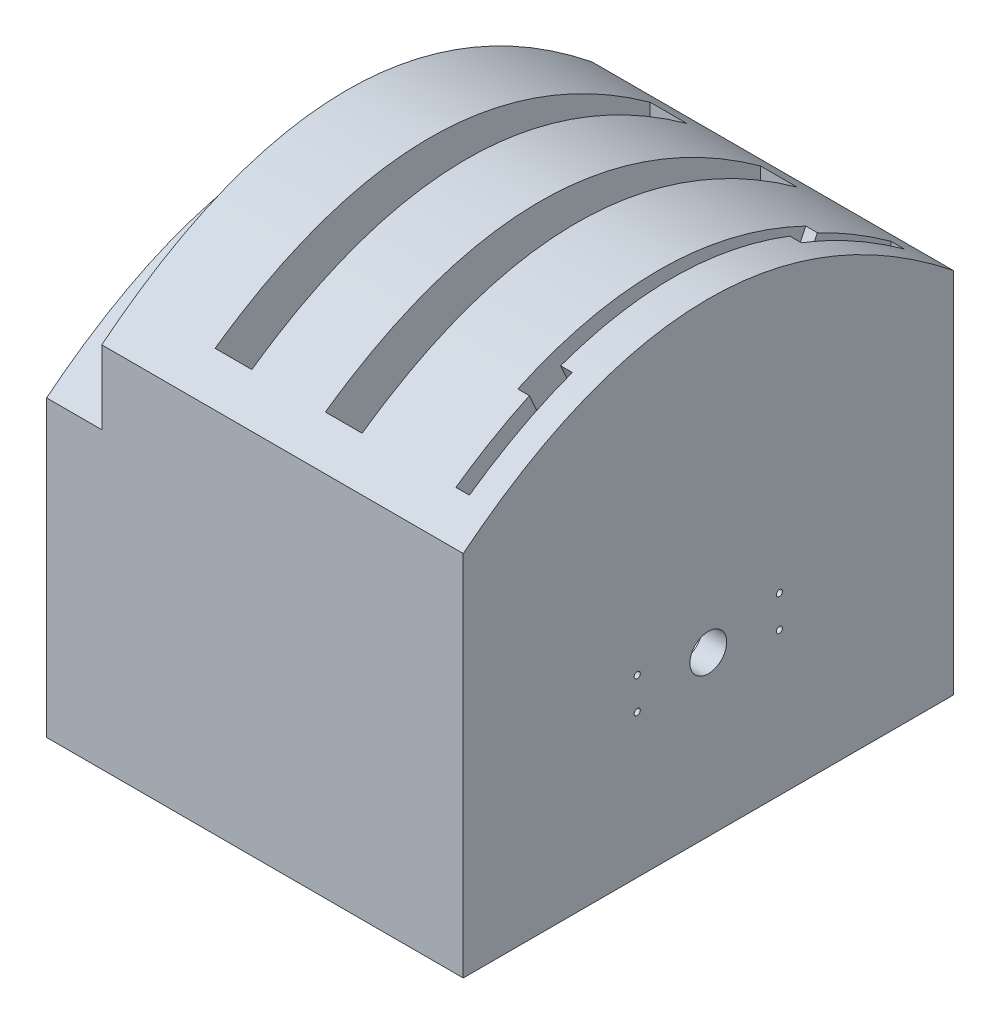
SolidWorks part; units mm, degrees
ref_plane "Front Plane" through (0, 0, 0) normal (0, 0, 1) x (1, 0, 0)
ref_plane "Top Plane" through (0, 0, 0) normal (0, 1, 0) x (1, 0, 0)
ref_plane "Right Plane" through (0, 0, 0) normal (1, 0, 0) x (0, 0, -1)
sketch "Sketch1" plane through (0, 0, 0) normal (1, 0, 0) x (0, 0, -1)
  line L2 (-100, 85) -> (-100, -65)
  line L3 (-100, -65) -> (100, -65)
  line L4 (100, 85) -> (100, -65)
  spline S0 degree 2 poles (-100, 85) (0, 165) (100, 85) knots 0 0 0 1 1 1
  point P4 (-100, 85)
  point P5 (100, 85)
  dimension "D1" = 200
  dimension "D2" = 100
  dimension "D3" = 150
  dimension "D4" = 150
  dimension "D5" = 40
  dimension "D6" = 100
  dimension "D7" = 125
extrude "Base" add sketch "Sketch1" along normal blind 170
ref_plane "New Top" through (0, 125, 0) normal (0, 1, 0) x (1, 0, 0)
sketch "Sketch3" plane through (0, 125, 0) normal (0, 1, 0) x (1, 0, 0)
  line L0 (170, -100) -> (170, 100) construction
  line L1 (116.25, 90) -> (101.25, 90)
  line L2 (116.25, 90) -> (116.25, -87.5)
  line L3 (116.25, -87.5) -> (101.25, -87.5)
  line L4 (101.25, 90) -> (101.25, -87.5)
  line L7 (170, 100) -> (0, 100) construction
  line L8 (71.25, 90) -> (56.25, 90)
  line L9 (71.25, 90) -> (71.25, -87.5)
  line L10 (71.25, -87.5) -> (56.25, -87.5)
  line L11 (56.25, 90) -> (56.25, -87.5)
  line L12 (170, -100) -> (0, -100) construction
  dimension "D1" = 53.75
  dimension "D2" = 15
  dimension "D3" = 30
  dimension "D4" = 15
  dimension "D5" = 10
  dimension "D6" = 12.5
  dimension "D7" = 12.5
  dimension "D8" = 10
sketch "Sketch4" plane through (0, 125, 0) normal (0, 1, 0) x (1, 0, 0)
  line L1 (22.5, 87.5) -> (10, 87.5)
  line L2 (22.5, 87.5) -> (22.5, -87.5)
  line L3 (22.5, -87.5) -> (10, -87.5)
  line L4 (10, 87.5) -> (10, -87.5)
  line L5 (170, 100) -> (0, 100) construction
  line L6 (170, -100) -> (0, -100) construction
  line L7 (0, 100) -> (0, -100) construction
  dimension "D1" = 10
  dimension "D2" = 12.5
  dimension "D3" = 12.5
  dimension "D4" = 12.5
sketch "Sketch5" plane through (0, 125, 0) normal (0, 1, 0) x (1, 0, 0)
  line L0 (170, -100) -> (170, 100) construction
  line L1 (160, 90) -> (154.5, 90)
  line L2 (160, 90) -> (160, 48)
  line L3 (160, -87.5) -> (154.5, -87.5)
  line L4 (149.75, 60) -> (149.75, -57.5)
  line L5 (170, 100) -> (0, 100) construction
  line L6 (170, -100) -> (0, -100) construction
  line L7 (160, -45.5) -> (160, -87.5)
  line L10 (149.75, 60) -> (154.5, 60)
  line L11 (154.5, 90) -> (154.5, 60)
  line L12 (160, 48) -> (155.25, 48)
  line L14 (160, -45.5) -> (155.25, -45.5)
  line L15 (155.25, 48) -> (155.25, -45.5)
  line L18 (149.75, -57.5) -> (154.5, -57.5)
  line L19 (154.5, -87.5) -> (154.5, -57.5)
  dimension "D1" = 5.5
  dimension "D3" = 10
  dimension "D4" = 12.5
  dimension "D5" = 10
  dimension "D6" = 30
  dimension "D7" = 30
  dimension "D8" = 5.5
  dimension "D9" = 12
  dimension "D10" = 12
  dimension "D11" = 5.5
extrude "Flaps Cut" cut sketch "Sketch5" against normal up to surface (190 mm away) up to face at (85, -65, 0)
extrude "Throttle Cut" cut sketch "Sketch3" against normal up to surface (190 mm away) up to face at (155.6667, -65, -1.25)
extrude "Wing Sweep Cut" cut sketch "Sketch4" against normal up to surface (190 mm away) up to face at (108.75, -65, -1.25)
sketch "Sketch7" plane through (0, -65, 0) normal (0, -1, 0) x (1, 0, 0)
  line L1 (10, 87.5) -> (160, 87.5)
  line L2 (10, 87.5) -> (10, -90)
  line L3 (10, -90) -> (160, -90)
  line L4 (160, 87.5) -> (160, -90)
extrude "Bottom Cut" cut sketch "Sketch7" against normal blind 140
sketch "Sketch6" plane through (0, 0, 0) normal (-1, 0, 0) x (0, 0, 1)
  circle A0 centre (0, 0) radius 7.5
  dimension "D1" = 15
  dimension "D2" = 0
extrude "Cut-Extrude1" cut sketch "Sketch6" against normal up to next from surface
sketch "Sketch8" plane through (170, 0, 0) normal (1, 0, 0) x (0, 0, -1)
  line L0 (-52.1418, 0) -> (41.3037, 0) construction
  circle A0 centre (-29, 6.5) radius 1.25
  circle A1 centre (29, 6.5) radius 1.25
  circle A2 centre (29, -6.5) radius 1.25
  circle A3 centre (-29, -6.5) radius 1.25
  dimension "D2" = 2.5
  dimension "D4" = 2.5
  dimension "D1" = 29
  dimension "D3" = 6.5
  dimension "D5" = 29
  dimension "D6" = 6.5
extrude "Cut-Extrude3" cut sketch "Sketch8" against normal blind 10
sketch "Sketch20" plane through (155.25, 0, 0) normal (-1, 0, 0) x (0, 0, 1)
  line L0 (45.5, 116.719) -> (23, 66.719)
  line L1 (23, 66.719) -> (45.5, 66.719)
  line L2 (45.5, 66.719) -> (45.5, 116.719)
  line L3 (-48, 115.784) -> (-48, 65.784)
  line L4 (-48, 65.784) -> (-24.5, 65.784)
  line L5 (-24.5, 65.784) -> (-48, 115.784)
  dimension "D1" = 90
  dimension "D2" = 22.5
  dimension "D3" = 50
  dimension "D4" = 50
  dimension "D5" = 23.5
extrude "Cut-Extrude10" cut sketch "Sketch20" against normal blind 4.75
sketch "Sketch22" plane through (160, 0, 0) normal (-1, 0, 0) x (0, 0, 1)
  line L0 (-60, 110.6) -> (-43, 75)
  line L2 (-43, 75) -> (-60, 75)
  line L3 (-60, 75) -> (-60, 110.6)
  line L4 (-60, 75) -> (-60, 110.6) construction
  line L5 (57.5, 111.775) -> (57.5, 75)
  line L11 (57.5, 75) -> (41.25, 75)
  line L12 (41.25, 75) -> (57.5, 111.775)
  line L13 (-90, 75) -> (-60, 75) construction
  line L14 (57.5, 75) -> (87.5, 75) construction
  point P4 (58.4459, 109.275)
  point P8 (0, 0)
  point P11 (57.654, 109.275)
  dimension "D1" = 0
  dimension "D2" = 17
  dimension "D3" = 90
  dimension "D4" = 0
  dimension "D5" = 16.25
  dimension "D6" = 0
  dimension "D7" = 0
  dimension "D8" = 0
extrude "Boss-Extrude5" add sketch "Sketch22" against normal blind 4.75 from surface at 10.25 starting at face at (149.75, 93.2406, 13.4375)
sketch "Sketch9" plane through (0, 0, 0) normal (-1, 0, 0) x (0, 0, 1)
  line L0 (100, 85) -> (100, -65) construction
  line L1 (-100, 55) -> (-100, 135)
  line L2 (-100, 135) -> (100, 135)
  line L3 (100, 135) -> (100, 55)
  spline S0 degree 2 poles (-100, 55) (0, 135) (100, 55) knots 0 0 0 1 1 1
  dimension "D1" = 100
  dimension "D2" = 40
  dimension "D3" = 100
  dimension "D4" = 40
  dimension "D5" = 0
  dimension "D6" = 30
  dimension "D7" = 80
extrude "Cut-Extrude4" cut sketch "Sketch9" against normal up to surface (22.5 mm away) up to face at (22.5, 84.6875, -21.875)
sketch "Sketch13" plane through (0, 75, 0) normal (0, -1, 0) x (1, 0, 0)
  line L1 (22.5, 87.5) -> (32.5, 87.5)
  line L2 (22.5, 87.5) -> (22.5, -90)
  line L3 (22.5, -90) -> (32.5, -90)
  line L4 (32.5, 87.5) -> (32.5, -90)
  dimension "D1" = 10
extrude "Boss-Extrude2" add sketch "Sketch13" along normal blind 140
sketch "Sketch12" plane through (22.5, 0, 0) normal (-1, 0, 0) x (0, 0, 1)
  line L0 (-48.4309, 58.2758) -> (-48.4309, 55.2758)
  line L1 (100, 27.75) -> (100, 24.75)
  spline S0 degree 3 poles (-48.4309, 58.2758) (3.558, 77.5898) (53.0349, 67.4145) (100, 27.75) knots 0.031016 0.031016 0.031016 0.031016 1 1 1 1
  spline S1 degree 3 poles (100, 24.75) (53.0349, 64.4145) (3.558, 74.5898) (-48.4309, 55.2758) knots 0 0 0 0 0.968984 0.968984 0.968984 0.968984
  point P0 (0, 64.75)
  point P2 (100, 24.75)
  point P4 (0, 67.75)
  point P5 (-100, 23.75)
  point P6 (100, 27.75)
  dimension "D1" = 100
  dimension "D4" = 40
  dimension "D5" = 40
  dimension "D6" = 100
  dimension "D8" = 27.25
  dimension "D9" = 3
extrude "Boss-Extrude1" add sketch "Sketch12" along normal blind 2.5
sketch "Sketch10" plane through (10, 0, 0) normal (1, 0, 0) x (0, 0, -1)
  circle A5 centre (0, -30) radius 7.5
  dimension "D1" = 15
  dimension "D6" = 30
extrude "Cut-Extrude5" cut sketch "Sketch10" along normal blind 10 from surface at 12.5 starting at face at (22.5, 38.6291, -3.176)
sketch "Sketch14" plane through (22.5, 0, 0) normal (-1, 0, 0) x (0, 0, 1)
  circle A0 centre (47.4611, -24.9378) radius 5
extrude "Cut-Extrude6" cut sketch "Sketch14" against normal blind 10
sketch "Sketch16" plane through (22.5, 0, 0) normal (-1, 0, 0) x (0, 0, 1)
  line L0 (-67.9611, -27.5) -> (138.1953, -27.5) construction
  circle A0 centre (80, -55) radius 1.25
  circle A1 centre (15, -55) radius 1.25
  circle A4 centre (15, 0) radius 1.25
  circle A5 centre (80, 0) radius 1.25
  dimension "D5" = 2.5
  dimension "D6" = 2.5
  dimension "D7" = 27.5
  dimension "D1" = 55
  dimension "D2" = 80
  dimension "D3" = 15
  dimension "D4" = 55
extrude "Cut-Extrude9" cut sketch "Sketch16" against normal blind 10
sketch "Sketch17" plane through (22.5, 0, 0) normal (-1, 0, 0) x (0, 0, 1)
  line L0 (-49.7797, 57.8455) -> (-56.5642, 70.771)
  line L1 (-56.5642, 70.771) -> (-59.2205, 69.3767)
  line L2 (-59.2205, 69.3767) -> (-51.0872, 53.8816)
  line L3 (-51.0872, 53.8816) -> (-48.4309, 55.2758)
  line L5 (-48.4309, 58.2758) -> (-49.7797, 57.8455)
  line L6 (-48.4309, 58.2758) -> (-48.4309, 55.2758)
  dimension "D1" = 90
  dimension "25" = 17.5
  dimension "D2" = 3
  dimension "D3" = 90
  dimension "D4" = 90
  dimension "D5" = 100
extrude "Boss-Extrude3" add sketch "Sketch17" along normal blind 2.5
sketch "Sketch19" plane through (22.5, 0, 0) normal (-1, 0, 0) x (0, 0, 1)
  line L0 (-100, -65) -> (-100, 55) construction
  line L1 (-55.7563, 69.232) -> (-56.9133, 71.6936)
  line L2 (-49.7797, 57.8455) -> (-56.5642, 70.771) construction
  line L3 (-100, 45.5) -> (-100, 42.5)
  spline S0 degree 2 poles (-100, 42.5) (-76.9596, 59.4626) (-55.7563, 69.232) knots 0 0 0 0.212033 0.212033 0.212033
  spline S1 degree 2 poles (-100, 45.5) (-77.5381, 61.9998) (-56.9133, 71.6936) knots 0 0 0 0.206248 0.206248 0.206248
  dimension "D6" = 12.5
  dimension "D4" = 26.732
  dimension "D3" = 2.7199
  dimension "D5" = 0
  dimension "D11" = 0
  dimension "D12" = 3
extrude "Boss-Extrude4" add sketch "Sketch19" along normal blind 2.5
fillet "Fillet1" radius 2.5 4 edges at (21.25, 53.8816, -51.0872) (21.25, 57.8455, -49.7797) (21.25, 67.954, -58.4737) (21.25, 71.6936, -56.9133)
